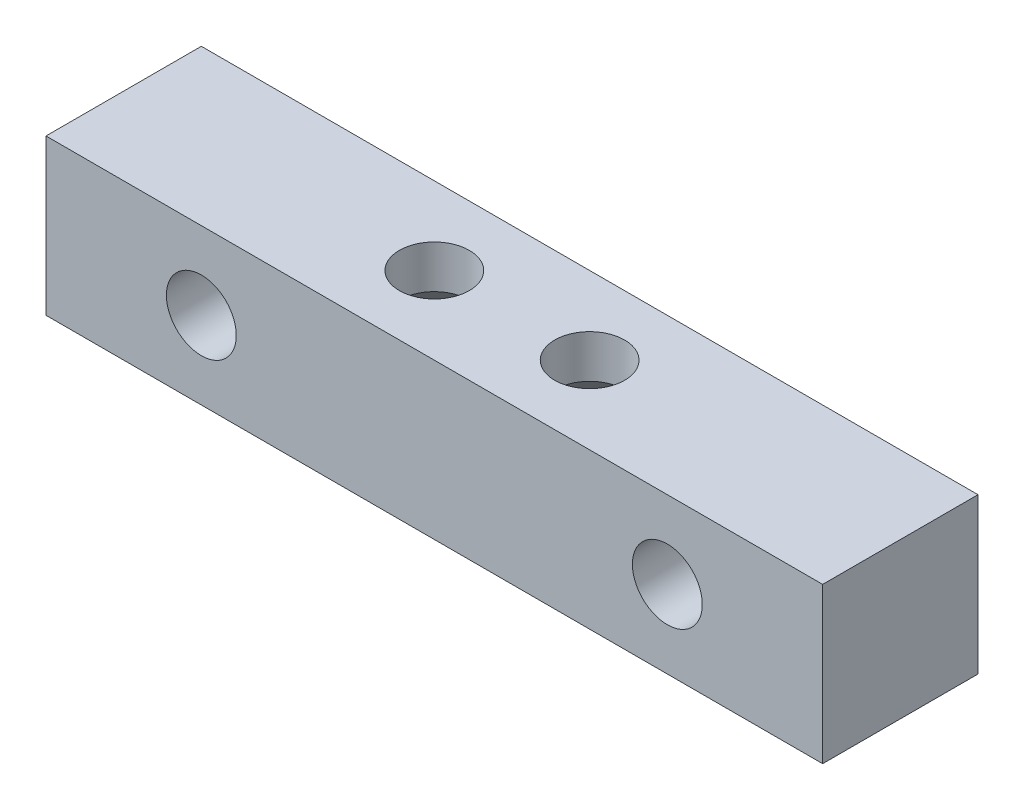
SolidWorks part; units mm, degrees
ref_plane "Front Plane" through (0, 0, 0) normal (0, 0, 1) x (1, 0, 0)
ref_plane "Top Plane" through (0, 0, 0) normal (0, 1, 0) x (1, 0, 0)
ref_plane "Right Plane" through (0, 0, 0) normal (1, 0, 0) x (0, 0, -1)
sketch "Sketch1" plane through (0, 0, 0) normal (0, 0, 1) x (1, 0, 0)
  line L1 (-25, -5) -> (25, -5)
  line L2 (-25, -5) -> (-25, 5)
  line L3 (-25, 5) -> (25, 5)
  line L4 (25, -5) -> (25, 5)
  line L5 (-25, -5) -> (25, 5) construction
  line L6 (-25, 5) -> (25, -5) construction
  point P0 (0, 0)
  dimension "D1" = 50
  dimension "D2" = 10
extrude "Boss-Extrude1" add sketch "Sketch1" along normal blind 10
hole_wizard "CSK for M4 SFHCS1" positions "Sketch8" profile "Sketch9" countersink size "M4" standard "ANSI Metric" end condition through all
sketch "Sketch8" plane through (0, -5, 0) normal (0, -1, 0) x (-1, 0, 0)
  line L0 (-5, -5) -> (5, -5)
  line L1 (25, 0) -> (-25, 0) construction
  point P0 (-5, -5)
  point P2 (5, -5)
  point P9 (0, -5)
  dimension "D1" = 10
  dimension "D2" = 5
sketch "Sketch9" plane through (5, -5, 5) normal (1, 0, 0) x (0, 0, -1)
  line L0 (0, 0) -> (0, 10)
  line L1 (0, 10) -> (2.25, 10)
  line L2 (2.25, 10) -> (2.25, 7.23)
  line L3 (2.25, 7.23) -> (4.48, 5)
  line L4 (4.48, 5) -> (4.48, 0)
  line L6 (4.48, 0) -> (0, 0)
  line L7 (-2.25, 7.23) -> (-4.48, 5) construction
  line L11 (0, -6.35) -> (0, 107.95) construction
  dimension "Thru Hole Dia." = 4.5
  dimension "Thru Hole Depth" = 10
  dimension "C'Sink Dia." = 8.96
  dimension "C'Sink Angle" = 90
  dimension "Head Clearance" = 5
hole_wizard "CBORE for M5 Hex Head Bolt1" positions "Sketch10" profile "Sketch11" counterbore size "M5" standard "ANSI Metric" end condition through all
sketch "Sketch10" plane through (0, 0, 0) normal (0, 0, -1) x (-1, 0, 0)
  line L0 (-15, 0) -> (15, 0)
  point P0 (-15, 0)
  point P1 (15, 0)
  point P8 (0, 0)
  dimension "D1" = 30
sketch "Sketch11" plane through (15, 0, 0) normal (1, 0, 0) x (0, 1, 0)
  line L0 (0, 0) -> (0, 10)
  line L1 (0, 10) -> (2.25, 10)
  line L3 (2.25, 10) -> (2.25, 4.2)
  line L4 (2.25, 4.2) -> (2.5, 4.2)
  line L5 (2.5, 4.2) -> (2.5, 0)
  line L7 (2.5, 0) -> (0, 0)
  line L11 (0, -6.35) -> (0, 107.95) construction
  dimension "Thru Hole Dia." = 4.5
  dimension "Thru Hole Depth" = 10
  dimension "C'Bore Dia." = 5
  dimension "C'Bore Depth" = 4.2
